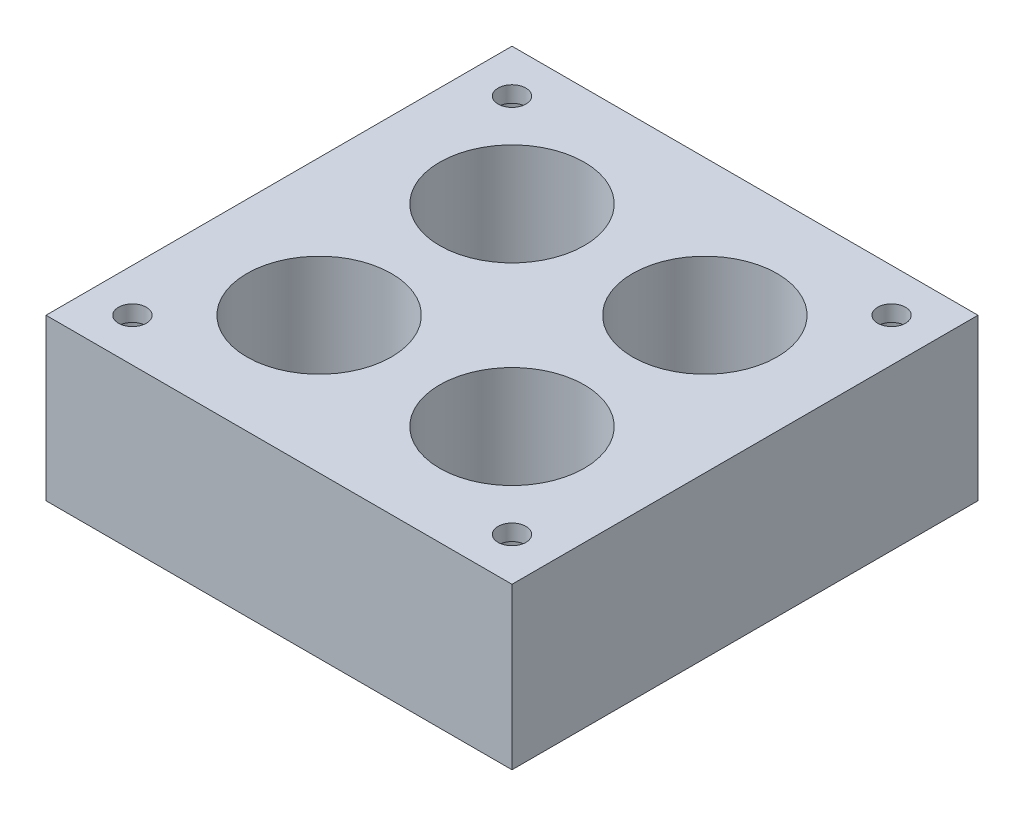
SolidWorks part; units mm, degrees
ref_plane "Front Plane" through (0, 0, 0) normal (0, 0, 1) x (1, 0, 0)
ref_plane "Top Plane" through (0, 0, 0) normal (0, 1, 0) x (1, 0, 0)
ref_plane "Right Plane" through (0, 0, 0) normal (1, 0, 0) x (0, 0, -1)
sketch "Sketch1" plane through (0, 0, 0) normal (0, 1, 0) x (1, 0, 0)
  line L0 (-1.4225, 15.1389) -> (-1.4225, -32.1148) construction
  line L1 (-19.8375, 15.1389) -> (16.9925, 15.1389)
  line L2 (-19.8375, 15.1389) -> (-19.8375, -21.6911)
  line L3 (-19.8375, -21.6911) -> (16.9925, -21.6911)
  line L4 (16.9925, 15.1389) -> (16.9925, -21.6911)
  line L5 (16.9925, -3.2761) -> (-38.4515, -3.2761) construction
  circle A0 centre (-16.4225, 11.7239) radius 1.1
  circle A1 centre (13.5775, 11.7239) radius 1.1
  circle A2 centre (13.5775, -18.2761) radius 1.1
  circle A3 centre (-16.4225, -18.2761) radius 1.1
  circle A4 centre (-9.0425, 4.3439) radius 2.159
  circle A5 centre (6.1975, 4.3439) radius 2.159
  circle A6 centre (6.1975, -10.8961) radius 2.159
  circle A7 centre (-9.0425, -10.8961) radius 2.159
  dimension "D3" = 2.2
  dimension "D4" = 30
  dimension "D6" = 4.318
  dimension "D1" = 36.83
  dimension "D2" = 36.83
  dimension "D5" = 30
  dimension "D7" = 15.24
  dimension "D8" = 15.24
extrude "Boss-Extrude1" add sketch "Sketch1" along normal blind 12.7
sketch "Sketch2" plane through (0, 12.7, 0) normal (0, 1, 0) x (1, 0, 0)
  line L0 (-1.4225, 15.1389) -> (-1.4225, -21.6911) construction
  line L1 (16.9925, 15.1389) -> (-19.8375, 15.1389) construction
  line L2 (-19.8375, -21.6911) -> (16.9925, -21.6911) construction
  line L3 (16.9925, -3.2761) -> (-19.8375, -3.2761) construction
  line L4 (16.9925, -21.6911) -> (16.9925, 15.1389) construction
  line L5 (-19.8375, 15.1389) -> (-19.8375, -21.6911) construction
  circle A0 centre (-9.0425, 4.3439) radius 5.715
  circle A1 centre (-9.0425, 4.3439) radius 2.159 construction
  circle A2 centre (6.1975, 4.3439) radius 5.715
  circle A3 centre (6.1975, -10.8961) radius 5.715
  circle A4 centre (-9.0425, -10.8961) radius 5.715
  dimension "D1" = 11.43
extrude "Cut-Extrude1" cut sketch "Sketch2" against normal blind 11.43
sketch "Sketch3" plane through (0, 0, 0) normal (0, -1, 0) x (1, 0, 0)
  line L0 (-1.4225, 21.6911) -> (-1.4225, -15.1389) construction
  line L1 (-19.8375, 21.6911) -> (16.9925, 21.6911) construction
  line L2 (16.9925, -15.1389) -> (-19.8375, -15.1389) construction
  line L3 (16.9925, 3.2761) -> (-19.8375, 3.2761) construction
  line L4 (16.9925, 21.6911) -> (16.9925, -15.1389) construction
  line L5 (-19.8375, -15.1389) -> (-19.8375, 21.6911) construction
  circle A0 centre (-16.4225, 18.2761) radius 2.54
  circle A1 centre (-16.4225, 18.2761) radius 1.1 construction
  circle A2 centre (13.5775, 18.2761) radius 2.54
  circle A3 centre (13.5775, -11.7239) radius 2.54
  circle A4 centre (-16.4225, -11.7239) radius 2.54
  dimension "D1" = 5.08
extrude "Cut-Extrude2" cut sketch "Sketch3" against normal blind 11.43
